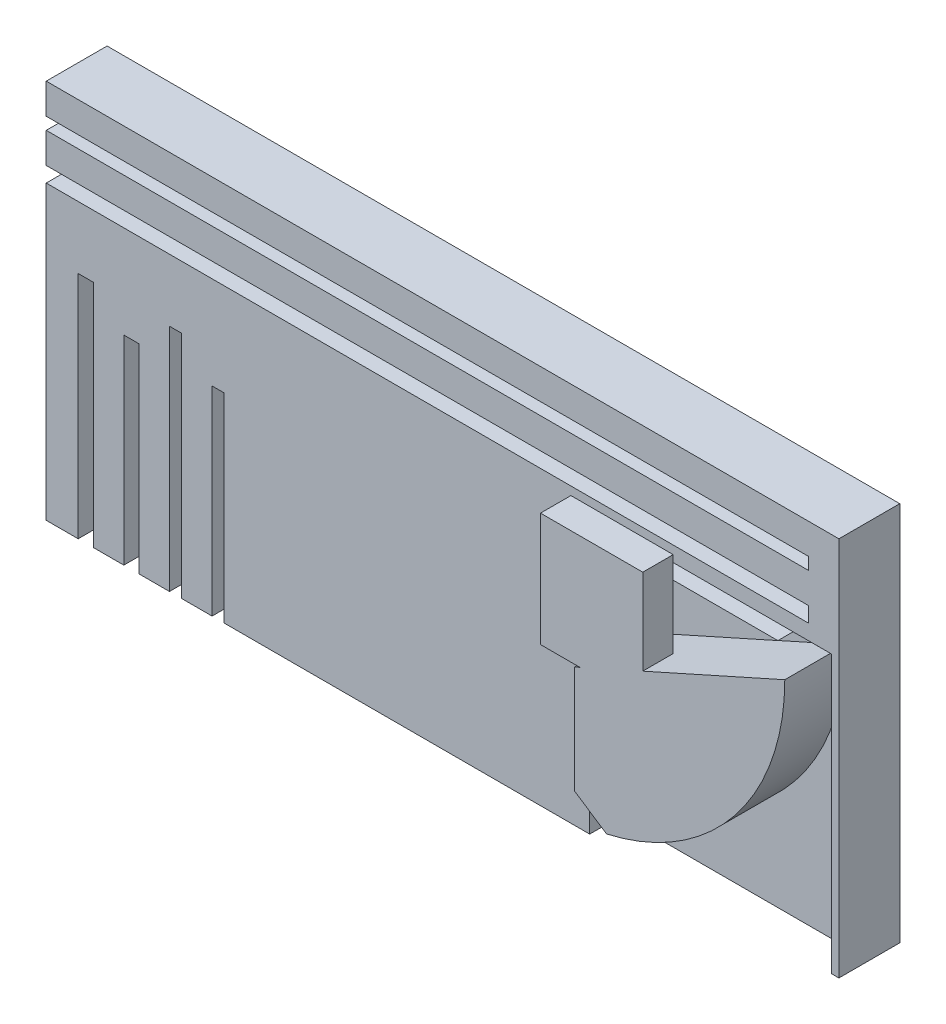
SolidWorks part; units mm, degrees
ref_plane "Alzado" through (0, 0, 0) normal (0, 0, 1) x (1, 0, 0)
ref_plane "Planta" through (0, 0, 0) normal (0, 1, 0) x (1, 0, 0)
ref_plane "Vista lateral" through (0, 0, 0) normal (1, 0, 0) x (0, 0, -1)
sketch "Croquis1" plane through (0, 0, 0) normal (0, 0, 1) x (1, 0, 0)
  line L1 (-54.2909, 30.4167) -> (7.7091, 30.4167)
  line L2 (-54.2909, 30.4167) -> (-54.2909, 5.4167)
  line L3 (-54.2909, 5.4167) -> (7.7091, 5.4167)
  line L4 (7.7091, 30.4167) -> (7.7091, 5.4167)
  dimension "D1" = 25
  dimension "D2" = 62
extrude "Saliente-Extruir1" add sketch "Croquis1" along normal blind 4
sketch "Croquis2" plane through (0, 0, 4) normal (0, 0, 1) x (1, 0, 0)
  line L0 (5.7091, 25.6167) -> (-44.3909, 25.6167)
  line L1 (-54.2909, 30.4167) -> (-54.2909, 5.4167) construction
  line L2 (5.7091, 25.6167) -> (5.7091, 24.6167)
  line L3 (-44.3909, 30.4167) -> (-44.3909, 28.4167)
  line L5 (7.2091, 23.6167) -> (-8.6699, 23.6167)
  line L6 (-42.2909, 5.4167) -> (-42.2909, 20.5167)
  line L7 (-54.2909, 5.4167) -> (7.7091, 5.4167) construction
  line L8 (-42.2909, 20.5167) -> (-41.2909, 20.5167)
  line L9 (-41.2909, 20.5167) -> (-41.2909, 5.4167)
  line L10 (-41.2909, 5.4167) -> (-42.2909, 5.4167)
  line L11 (-39.2909, 5.4167) -> (-39.2909, 18.5167)
  line L12 (-39.2909, 18.5167) -> (-38.2909, 18.5167)
  line L13 (-38.2909, 18.5167) -> (-38.2909, 5.4167)
  line L14 (-38.2909, 5.4167) -> (-39.2909, 5.4167)
  line L15 (5.7091, 28.4167) -> (-44.3909, 28.4167)
  line L16 (5.7091, 27.6167) -> (5.7091, 28.4167)
  line L17 (-44.3909, 27.6167) -> (-44.3909, 25.6167)
  line L18 (7.7091, 5.4167) -> (7.7091, 30.4167) construction
  line L19 (-36.2909, 5.4167) -> (-36.2909, 20.5167)
  line L20 (-36.2909, 20.5167) -> (-35.4909, 20.5167)
  line L21 (-35.4909, 20.5167) -> (-35.4909, 5.4167)
  line L22 (-35.4909, 5.4167) -> (-36.2909, 5.4167)
  line L23 (-33.4909, 5.4167) -> (-33.4909, 18.5167)
  line L24 (-33.4909, 18.5167) -> (-32.6909, 18.5167)
  line L25 (-32.6909, 18.5167) -> (-32.6909, 5.4167)
  line L26 (-32.6909, 5.4167) -> (-33.4909, 5.4167)
  line L27 (-44.3909, 27.6167) -> (5.7091, 27.6167)
  line L28 (-44.3909, 24.6167) -> (5.7091, 24.6167)
  line L30 (-54.2909, 30.4167) -> (-44.3909, 30.4167)
  line L31 (-54.2909, 30.4167) -> (-54.2909, 5.4167)
  line L32 (-54.2909, 5.4167) -> (-44.3909, 5.4167)
  line L33 (-44.3909, 24.6167) -> (-44.3909, 5.4167)
  line L39 (6.1523, 22.6167) -> (-7.6699, 16.4284)
  line L40 (-7.6699, 22.6167) -> (3.6964, 22.6167)
  line L41 (-8.6699, 5.4167) -> (7.2091, 5.4167)
  line L43 (-8.6699, 22.2077) -> (-8.6699, 23.6167)
  line L44 (-7.6699, 17.5279) -> (-7.6699, 22.6167)
  line L45 (-8.6699, 22.2077) -> (-8.6699, 5.4167)
  line L47 (-7.6699, 9.3749) -> (-7.6699, 16.4284)
  line L48 (-7.6699, 17.5279) -> (3.6964, 22.6167)
  line L49 (-7.6699, 9.3749) -> (-5.5666, 7.9799)
  line L51 (7.2091, 5.4167) -> (7.2091, 23.6167)
  arc A0 (6.1523, 22.6167) -> (-5.5666, 7.9799) centre (-8.8477, 22.6167) cw
  dimension "D1" = 2
  dimension "D3" = 2
  dimension "D4" = 12
  dimension "D5" = 1
  dimension "D6" = 15.1
  dimension "D7" = 1
  dimension "D8" = 13.1
  dimension "D9" = 1
  dimension "D10" = 0.8
  dimension "D11" = 0.8
  dimension "D12" = 2
  dimension "D13" = 2
  dimension "D14" = 2
  dimension "D15" = 0.8
  dimension "D16" = 15
  dimension "D23" = 1
  dimension "D25" = 1
extrude "Cortar-Extruir1" cut sketch "Croquis2" against normal blind 2
sketch "Croquis4" plane through (0, 0, 4) normal (0, 0, 1) x (1, 0, 0)
  line L0 (-5.5666, 7.9799) -> (-7.6699, 9.3749)
  line L1 (-7.6699, 9.3749) -> (-7.6699, 16.4284)
  line L2 (-7.6699, 16.4284) -> (6.1523, 22.6167)
  arc A0 (-5.5666, 7.9799) -> (6.1523, 22.6167) centre (-8.8477, 22.6167) ccw construction
  arc A1 (6.1523, 22.6167) -> (-5.5666, 7.9799) centre (-8.8477, 22.6167) cw
extrude "Saliente-Extruir7" add sketch "Croquis4" along normal blind 2
sketch "Croquis6" plane through (0, 0, 4) normal (0, 0, 1) x (1, 0, 0)
  line L1 (-9.905, 24.0704) -> (-3.183, 24.0704)
  line L2 (-9.905, 24.0704) -> (-9.905, 16.5883)
  line L3 (-9.905, 16.5883) -> (-3.183, 16.5883)
  line L4 (-3.183, 24.0704) -> (-3.183, 16.5883)
extrude "Saliente-Extruir8" add sketch "Croquis6" along normal blind 2
sketch "Croquis7" plane through (0, 0, 2) normal (0, 0, 1) x (1, 0, 0)
  line L1 (-54.2909, 30.4167) -> (-44.3909, 30.4167)
  line L2 (-54.2909, 30.4167) -> (-54.2909, 5.4167)
  line L3 (-54.2909, 5.4167) -> (-44.3909, 5.4167)
  line L4 (-44.3909, 30.4167) -> (-44.3909, 5.4167)
extrude "Cortar-Extruir2" cut sketch "Croquis7" against normal blind 2
